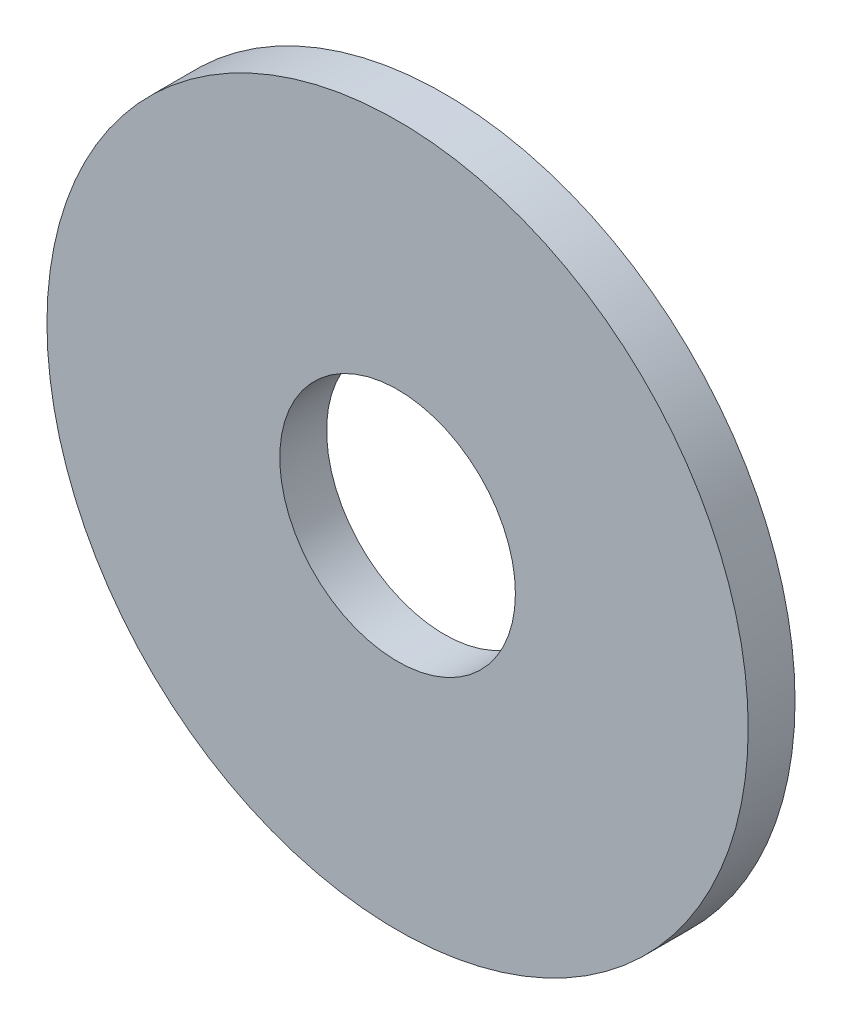
SolidWorks part; units mm, degrees
ref_plane "前视基准面" through (0, 0, 0) normal (0, 0, 1) x (1, 0, 0)
ref_plane "上视基准面" through (0, 0, 0) normal (0, 1, 0) x (1, 0, 0)
ref_plane "右视基准面" through (0, 0, 0) normal (1, 0, 0) x (0, 0, -1)
sketch "草图1" plane through (0, 0, 0) normal (0, 0, 1) x (1, 0, 0)
  circle A0 centre (0, 0) radius 14.97
  circle A1 centre (0, 0) radius 5.03
  dimension "D1" = 29.94
  dimension "D2" = 10.06
extrude "凸台-拉伸1" add sketch "草图1" along normal blind 2 contours A0
